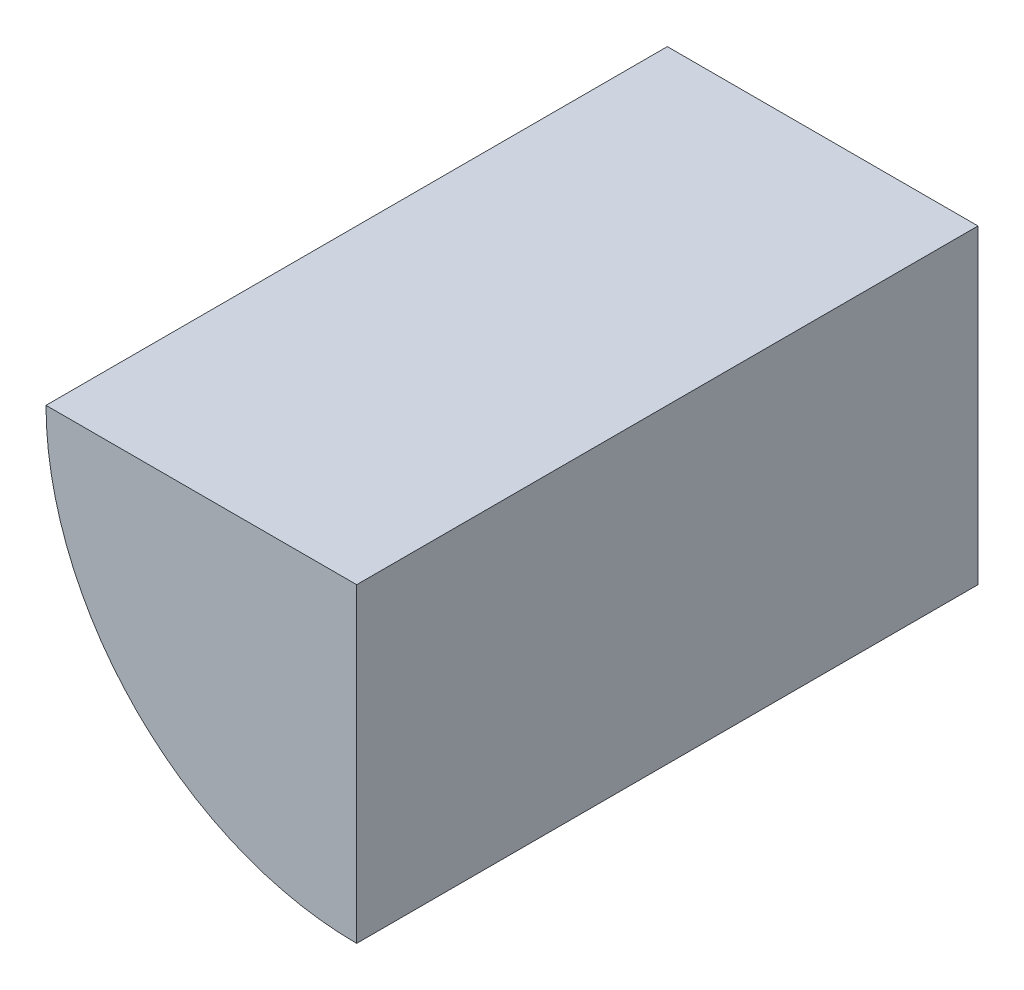
SolidWorks part; units mm, degrees
ref_plane "Alzado" through (0, 0, 0) normal (0, 0, 1) x (1, 0, 0)
ref_plane "Planta" through (0, 0, 0) normal (0, 1, 0) x (1, 0, 0)
ref_plane "Vista lateral" through (0, 0, 0) normal (1, 0, 0) x (0, 0, -1)
sketch "Croquis1" plane through (0, 0, 0) normal (0, 0, 1) x (1, 0, 0)
  line L0 (0, 0) -> (0, -25)
  line L1 (-25, 0) -> (0, 0)
  arc A0 (-25, 0) -> (0, -25) centre (0, 0) ccw
  dimension "D1" = 50
extrude "Saliente-Extruir1" add sketch "Croquis1" along normal blind 50
sketch "Croquis2" plane through (0, 0, 0) normal (0, 0, -1) x (-1, 0, 0)
  circle A0 centre (10.5645, -9.6633) radius 5
  dimension "D1" = 10
extrude "Cortar-Extruir1" cut sketch "Croquis2" against normal blind 10
